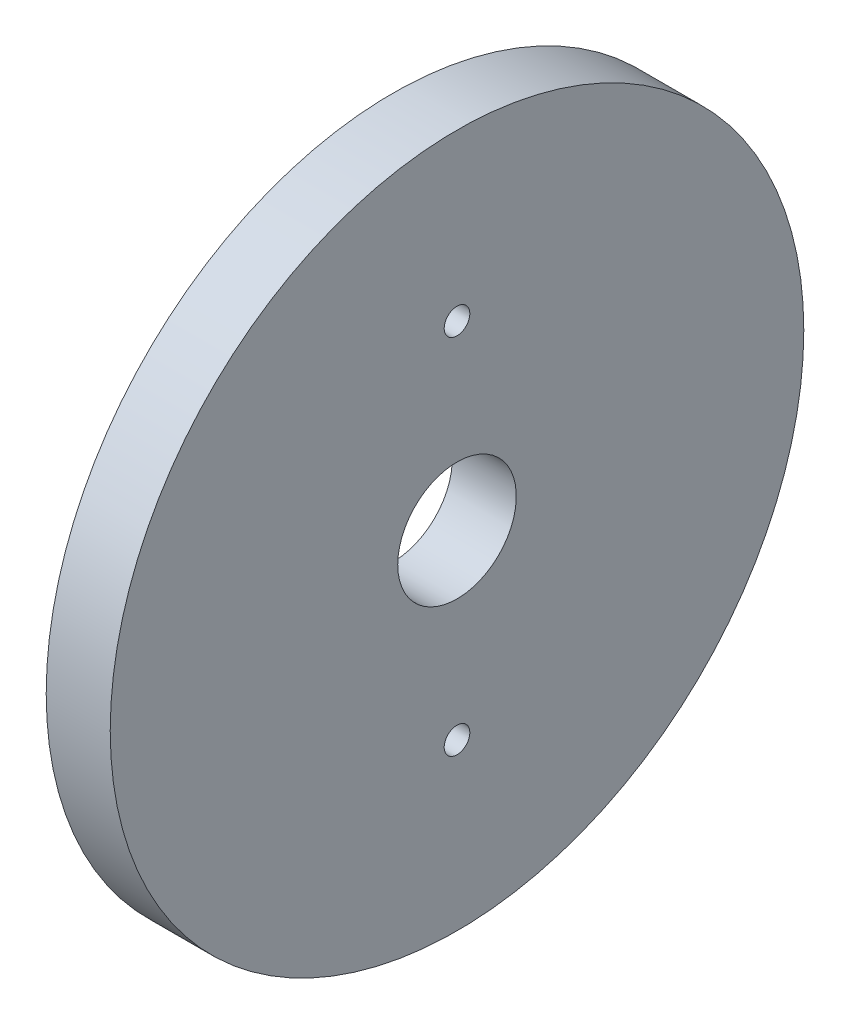
SolidWorks part; units mm, degrees
ref_plane "Front Plane" through (0, 0, 0) normal (0, 0, 1) x (1, 0, 0)
ref_plane "Top Plane" through (0, 0, 0) normal (0, 1, 0) x (1, 0, 0)
ref_plane "Right Plane" through (0, 0, 0) normal (1, 0, 0) x (0, 0, -1)
sketch "Axial profile (mm)" plane through (0, 0, 0) normal (0, 0, 1) x (1, 0, 0)
  line L0 (-110, 0) -> (75, 0) construction
  line L1 (13.7, 11.1125) -> (25.7, 11.1125)
  line L2 (25.7, 11.1125) -> (25.7, 65)
  line L3 (25.7, 65) -> (13.7, 65)
  line L4 (13.7, 65) -> (13.7, 11.1125)
revolve "Full revolution" add sketch "Axial profile (mm)" angle 360 about L0
sketch "Sketch2" plane through (0, 0, 0) normal (1, 0, 0) x (0, 0, -1)
  circle A0 centre (0, 34) radius 2.4
  circle A1 centre (0, -34) radius 2.4
extrude "Axial holes" cut sketch "Sketch2" along normal through all and the other way through all
